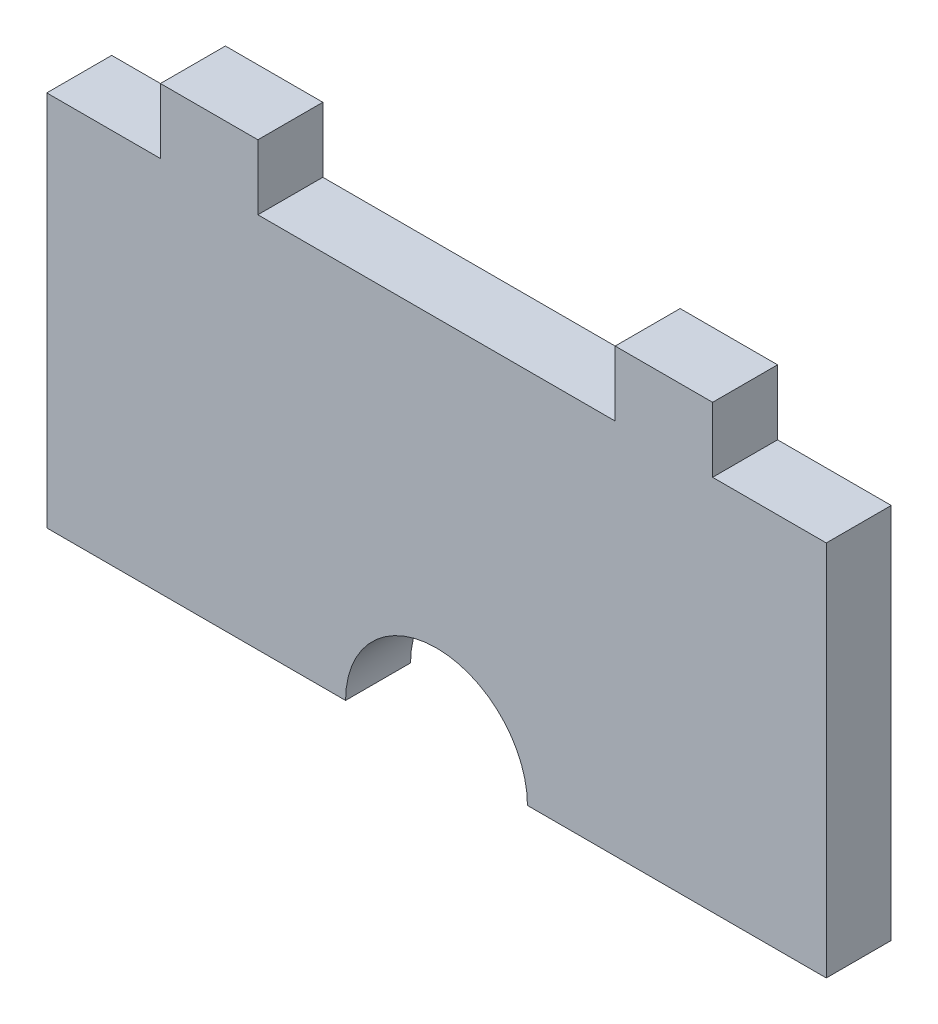
SolidWorks part; units mm, degrees
material "Acrylic (Medium-high impact)"
ref_plane "Front Plane" through (0, 0, 0) normal (0, 0, 1) x (1, 0, 0)
ref_plane "Top Plane" through (0, 0, 0) normal (0, 1, 0) x (1, 0, 0)
ref_plane "Right Plane" through (0, 0, 0) normal (1, 0, 0) x (0, 0, -1)
sketch "Sketch1" plane through (0, 0, 0) normal (0, 0, 1) x (1, 0, 0)
  line L0 (-76.2, 142.24) -> (-25.4, 142.24) construction
  line L1 (-76.2, 215.9) -> (-53.975, 215.9)
  line L2 (-76.2, 215.9) -> (-76.2, 142.24)
  line L3 (-76.2, 142.24) -> (-76.2, 215.9) construction
  line L4 (76.2, 215.9) -> (76.2, 142.24)
  line L10 (34.925, 215.9) -> (34.925, 228.6) construction
  line L11 (53.975, 228.6) -> (34.925, 228.6) construction
  line L12 (53.975, 215.9) -> (53.975, 228.6) construction
  line L13 (-34.925, 215.9) -> (-34.925, 228.6) construction
  line L14 (-34.925, 228.6) -> (-53.975, 228.6) construction
  line L15 (-53.975, 215.9) -> (-53.975, 228.6) construction
  line L16 (-34.925, 215.9) -> (34.925, 215.9)
  line L17 (53.975, 215.9) -> (76.2, 215.9)
  line L18 (-76.2, 142.24) -> (76.2, 142.24)
  line L19 (34.925, 215.9) -> (34.925, 228.6)
  line L20 (53.975, 228.6) -> (34.925, 228.6)
  line L21 (53.975, 215.9) -> (53.975, 228.6)
  line L22 (-34.925, 215.9) -> (-34.925, 228.6)
  line L23 (-34.925, 228.6) -> (-53.975, 228.6)
  line L24 (-53.975, 215.9) -> (-53.975, 228.6)
extrude "Extrude1" add sketch "Sketch1" against normal blind 12.7
sketch "Sketch2" plane through (0, 0, 0) normal (0, 0, 1) x (1, 0, 0)
  arc A1 (17.78, 142.24) -> (-17.78, 142.24) centre (0, 142.24) ccw construction
  circle A3 centre (0, 142.24) radius 17.78
extrude "Cut-Extrude1" cut sketch "Sketch2" against normal through all
